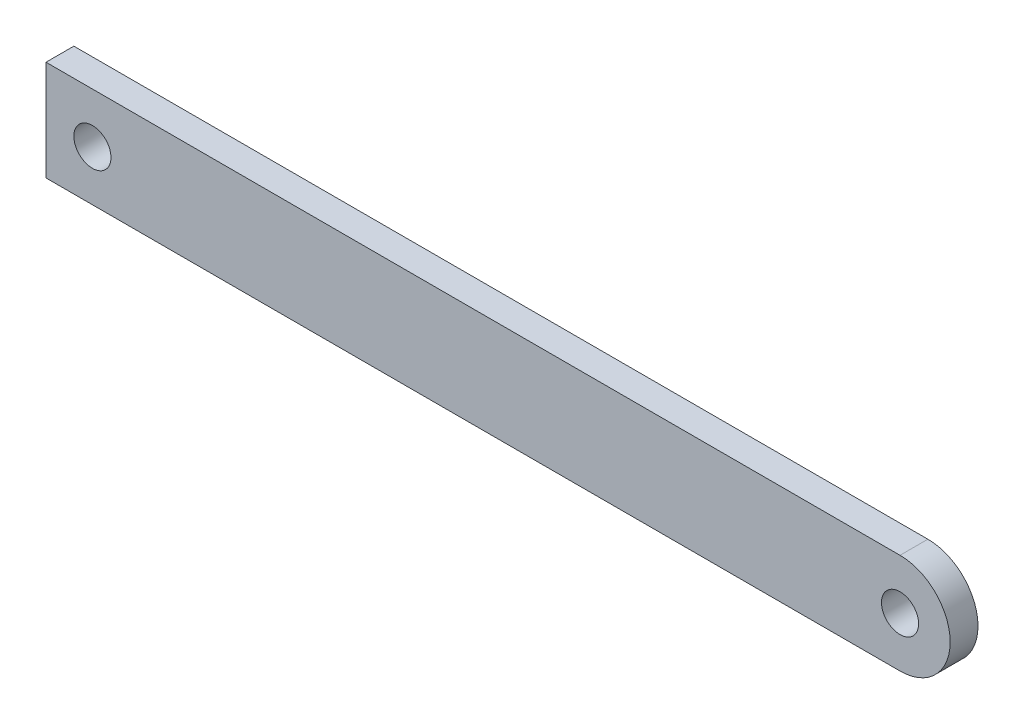
SolidWorks part; units mm, degrees
material "6061 Alloy"
ref_plane "Front Plane" through (0, 0, 0) normal (0, 0, 1) x (1, 0, 0)
ref_plane "Top Plane" through (0, 0, 0) normal (0, 1, 0) x (1, 0, 0)
ref_plane "Right Plane" through (0, 0, 0) normal (1, 0, 0) x (0, 0, -1)
sketch "Sketch2" plane through (0, 0, 0) normal (0, 0, 1) x (1, 0, 0)
  line L0 (0, 0) -> (0, 85672.5492) construction
  line L1 (0, 0) -> (85672.5492, 0) construction
  line L2 (-230, 27) -> (230, 27)
  line L3 (-230, -27) -> (230, -27)
  line L4 (-230, -27) -> (-230, 27)
  arc A0 (230, 27) -> (230, -27) centre (230, 0) cw
  circle A3 centre (230, 0) radius 10
  circle A4 centre (-205, 0) radius 10
  point P8 (0, 27)
  dimension "D3" = 20
  dimension "D4" = 20
  dimension "D1" = 460
  dimension "D2" = 54
  dimension "D5" = 25
extrude "Boss-Extrude2" add sketch "Sketch2" against normal blind 15
